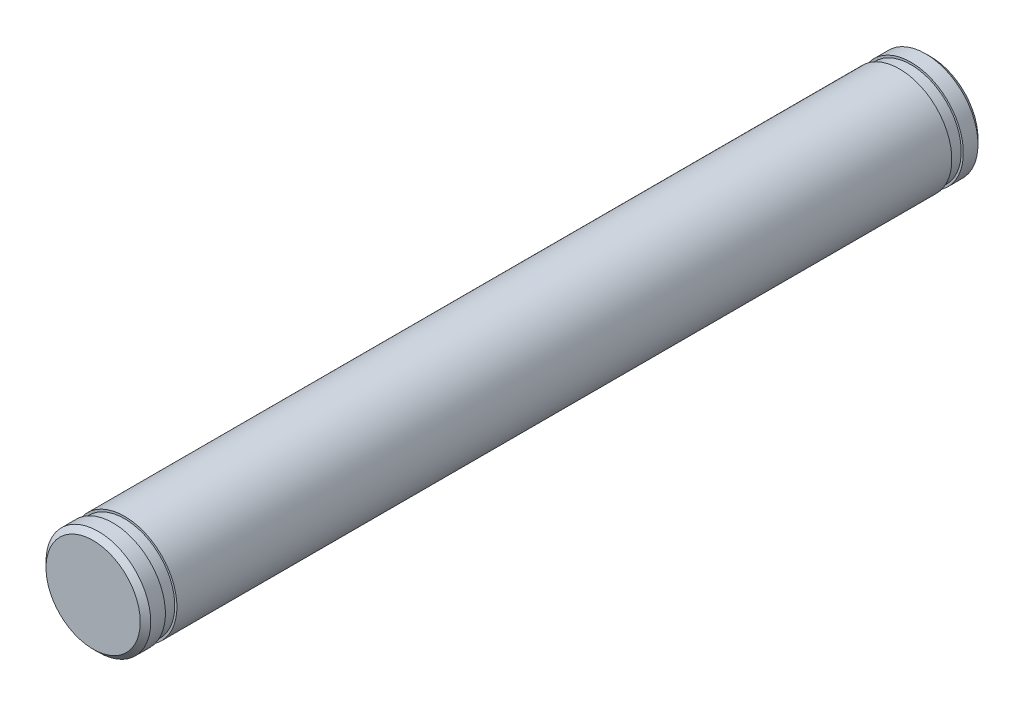
SolidWorks part; units mm, degrees
ref_plane "前视基准面" through (0, 0, 0) normal (0, 0, 1) x (1, 0, 0)
ref_plane "上视基准面" through (0, 0, 0) normal (0, 1, 0) x (1, 0, 0)
ref_plane "右视基准面" through (0, 0, 0) normal (1, 0, 0) x (0, 0, -1)
other "Configuration Table"
sketch "草图1" plane through (0, 0, 0) normal (0, 0, 1) x (1, 0, 0)
  circle A0 centre (0, 0) radius 5
  dimension "D1" = 10
extrude "凸台-拉伸1" add sketch "草图1" along normal blind 80
chamfer "倒角1" distance 0.5 angle 45 2 edges at (5, 0, 80) (5, 0, 0)
ref_plane "基准面1" through (0, 0, 40) normal (0, 0, 1) x (1, 0, 0)
sketch "草图2" plane through (0, 0, 0) normal (0, 0, -1) x (-1, 0, 0)
  circle A0 centre (0, 0) radius 5 construction
  circle A1 centre (0, 0) radius 5
  circle A2 centre (0, 0) radius 4.8
  dimension "D1" = 9.6
extrude "切除-拉伸1" cut sketch "草图2" along normal blind 1.1 from offset 3 offset against normal yes
mirror "镜向1" about plane through (0, 0, 40) normal (0, 0, 1) of "切除-拉伸1"
